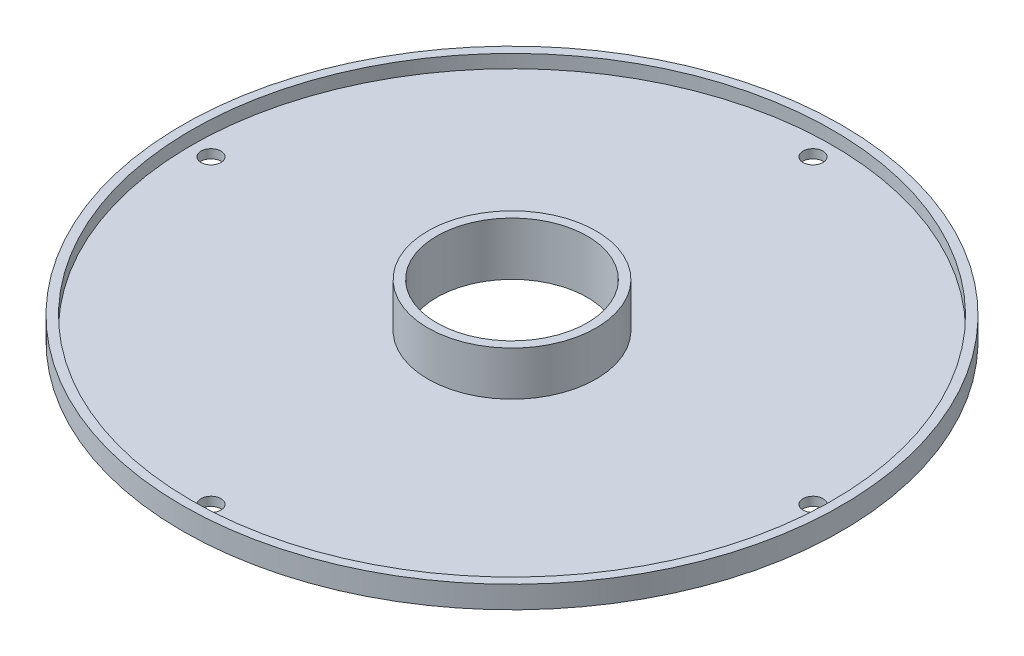
SolidWorks part; units mm, degrees
ref_plane "Front Plane" through (0, 0, 0) normal (0, 0, 1) x (1, 0, 0)
ref_plane "Top Plane" through (0, 0, 0) normal (0, 1, 0) x (1, 0, 0)
ref_plane "Right Plane" through (0, 0, 0) normal (1, 0, 0) x (0, 0, -1)
sketch "Sketch1" plane through (0, 0, 0) normal (0, 1, 0) x (1, 0, 0)
  circle A0 centre (0, 0) radius 74.45
  circle A1 centre (68, 0) radius 2.25
  circle A2 centre (0, -68) radius 2.25
  circle A3 centre (-68, 0) radius 2.25
  circle A4 centre (0, 68) radius 2.25
  circle A5 centre (0, 0) radius 17
  dimension "D1" = 148.9
  dimension "D2" = 4.5
  dimension "D5" = 34
  dimension "D3" = 68
  dimension "D4" = 4
extrude "Boss-Extrude1" add sketch "Sketch1" along normal blind 2
sketch "Sketch2" plane through (0, 2, 0) normal (0, 1, 0) x (1, 0, 0)
  circle A0 centre (0, 0) radius 17 construction
  circle A1 centre (0, 0) radius 17
  circle A2 centre (0, 0) radius 19
  dimension "D1" = 2
extrude "Boss-Extrude2" add sketch "Sketch2" along normal blind 10
sketch "Sketch3" plane through (0, 2, 0) normal (0, 1, 0) x (1, 0, 0)
  circle A1 centre (0, 0) radius 72.45
  circle A2 centre (0, 0) radius 74.45 construction
  circle A3 centre (0, 0) radius 74.45
  dimension "D2" = 2
extrude "Boss-Extrude3" add sketch "Sketch3" along normal blind 3 contours A3
